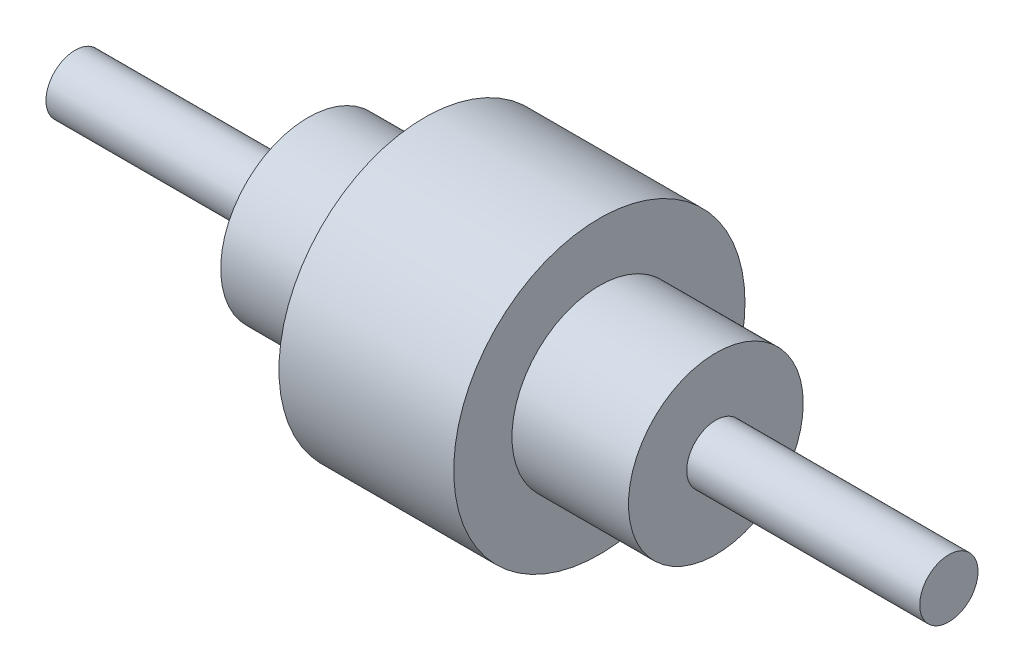
SolidWorks part; units mm, degrees
ref_plane "Front Plane" through (0, 0, 0) normal (0, 0, 1) x (1, 0, 0)
ref_plane "Top Plane" through (0, 0, 0) normal (0, 1, 0) x (1, 0, 0)
ref_plane "Right Plane" through (0, 0, 0) normal (1, 0, 0) x (0, 0, -1)
sketch "Sketch1" plane through (0, 0, 0) normal (1, 0, 0) x (0, 0, -1)
  circle A0 centre (0, 0) radius 254
  dimension "D1" = 508
extrude "Boss-Extrude1" add sketch "Sketch1" along normal blind 2032
sketch "Sketch3" plane through (2032, 0, 0) normal (1, 0, 0) x (0, 0, -1)
  circle A0 centre (0, 0) radius 762
  dimension "D1" = 1524
extrude "Boss-Extrude2" add sketch "Sketch3" along normal blind 1016
sketch "Sketch4" plane through (3048, 0, 0) normal (1, 0, 0) x (0, 0, -1)
  circle A0 centre (0, 0) radius 1270
  dimension "D1" = 2540
extrude "Boss-Extrude3" add sketch "Sketch4" along normal blind 1524
sketch "Sketch5" plane through (4572, 0, 0) normal (1, 0, 0) x (0, 0, -1)
  circle A0 centre (0, 0) radius 762
  dimension "D1" = 1524
extrude "Boss-Extrude4" add sketch "Sketch5" along normal blind 1016
sketch "Sketch6" plane through (5588, 0, 0) normal (1, 0, 0) x (0, 0, -1)
  circle A0 centre (0, 0) radius 254
  dimension "D1" = 508
extrude "Boss-Extrude5" add sketch "Sketch6" along normal blind 2032
